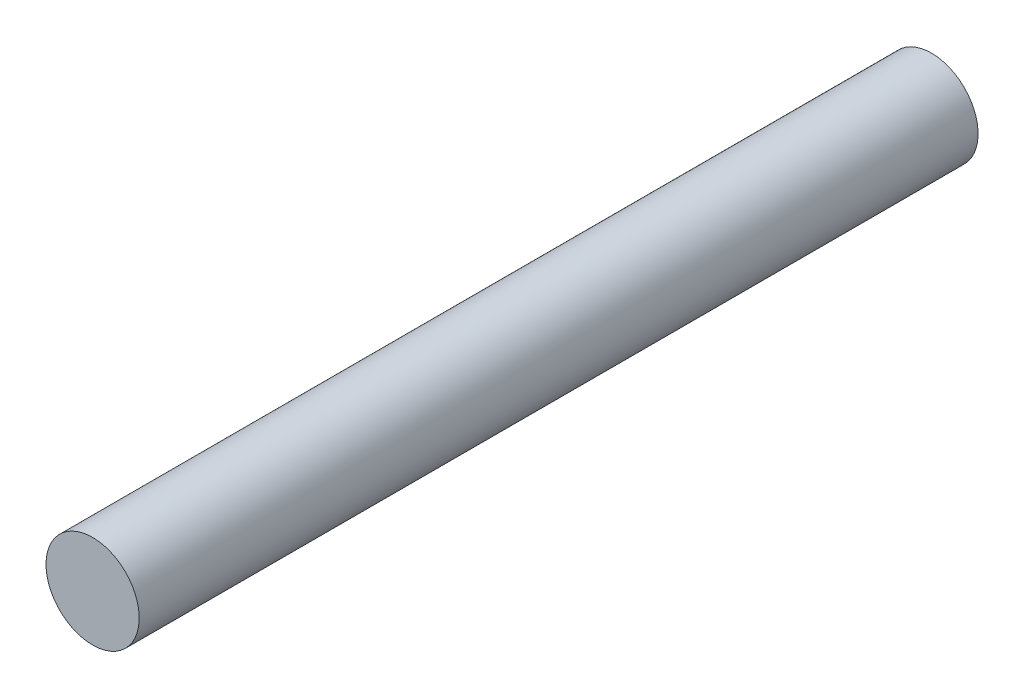
SolidWorks part; units mm, degrees
ref_plane "前视基准面" through (0, 0, 0) normal (0, 0, 1) x (1, 0, 0)
ref_plane "上视基准面" through (0, 0, 0) normal (0, 1, 0) x (1, 0, 0)
ref_plane "右视基准面" through (0, 0, 0) normal (1, 0, 0) x (0, 0, -1)
sketch "草图1" plane through (0, 0, 0) normal (0, 0, 1) x (1, 0, 0)
  circle A0 centre (0, 0) radius 5
  dimension "D1" = 10
extrude "凸台-拉伸1" add sketch "草图1" along normal blind 90
